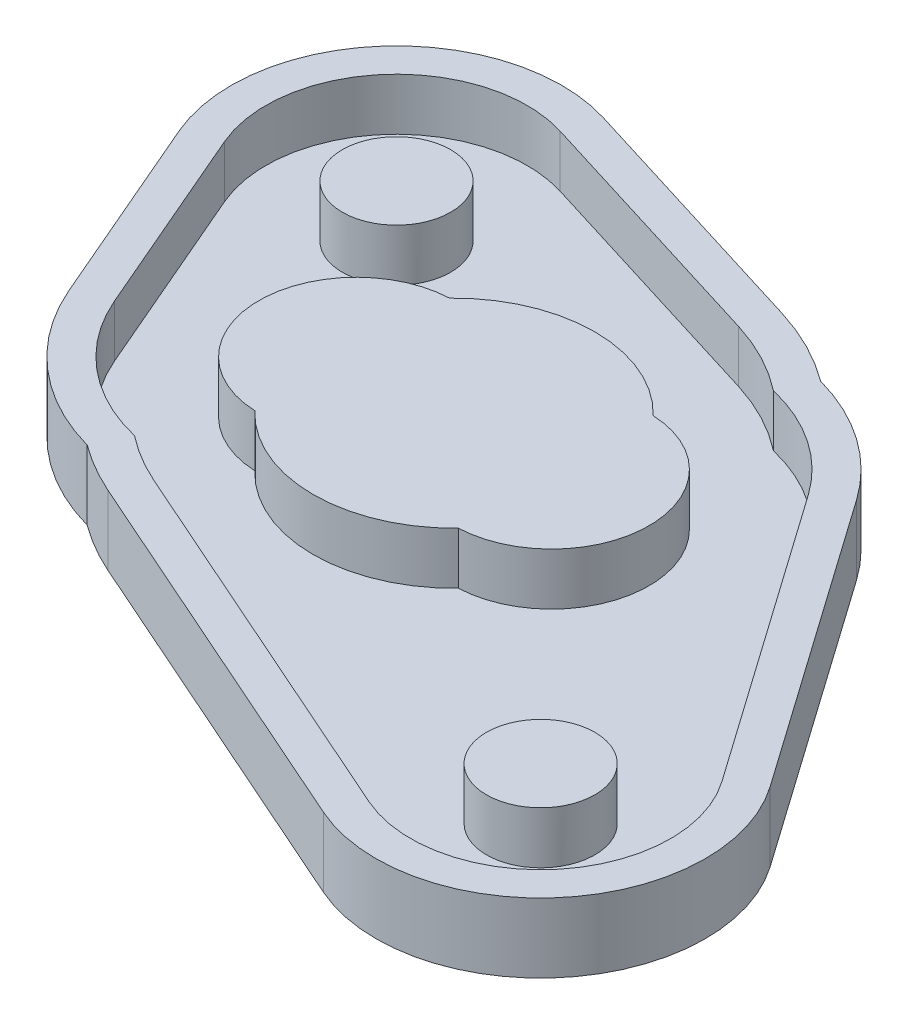
SolidWorks part; units mm, degrees
ref_plane "Front Plane" through (0, 0, 0) normal (0, 0, 1) x (1, 0, 0)
ref_plane "Top Plane" through (0, 0, 0) normal (0, 1, 0) x (1, 0, 0)
ref_plane "Right Plane" through (0, 0, 0) normal (1, 0, 0) x (0, 0, -1)
sketch "Sketch1" plane through (0, 0, 0) normal (0, 1, 0) x (1, 0, 0)
  line L0 (-5.625, 0) -> (5.625, 0) construction
  line L1 (0, 0) -> (0, 8.125) construction
  line L2 (0, -8.125) -> (0, -13.125) construction
  line L3 (-5.3106, -12.0026) -> (16.9654, -21.8587)
  line L4 (14.3146, 6.114) -> (26.1338, -10.6842)
  line L5 (12.5, -15) -> (20, -15) construction
  line L6 (-11.25, 0) -> (-13.2554, 0) construction
  line L7 (0, 8.125) -> (0, 9.9416) construction
  line L8 (20, -15) -> (0, 0) construction
  line L9 (0, 0) -> (-23.6642, 17.7481) construction
  line L10 (0, 0) -> (-14.4563, 10.8423) construction
  line L11 (0, 9.9416) -> (-13.2554, 9.9416) construction
  line L12 (-13.2554, 9.9416) -> (-13.2554, 0) construction
  line L13 (-20.1848, 6.9615) -> (-15.3857, -4.1977)
  line L14 (-11.0271, 17.1479) -> (3.8773, 12.5392)
  line L15 (-6.1198, -13.8316) -> (16.1562, -23.6876)
  line L16 (15.9503, 7.2649) -> (27.7695, -9.5334)
  line L17 (-10.4363, 19.0586) -> (4.4681, 14.45)
  line L18 (-22.0221, 6.1714) -> (-17.2229, -4.9878)
  arc A0 (-5.8681, -5.6197) -> (5.8681, -5.6197) centre (0, 0) ccw
  arc A1 (5.8681, -5.6197) -> (5.8681, 5.6197) centre (5.625, 0) ccw
  arc A2 (-5.8681, -5.6197) -> (-5.8681, 5.6197) centre (-5.625, 0) cw
  arc A3 (5.8681, 5.6197) -> (-5.8681, 5.6197) centre (0, 0) ccw
  arc A4 (14.3146, 6.114) -> (8.0903, 10.335) centre (5.625, 0) ccw
  arc A5 (8.0903, 10.335) -> (3.8773, 12.5392) centre (0, 0) ccw
  arc A6 (-8.0903, -10.335) -> (-15.3857, -4.1977) centre (-5.625, 0) cw
  arc A7 (-8.0903, -10.335) -> (-5.3106, -12.0026) centre (0, 0) ccw
  circle A8 centre (20, -15) radius 3.125
  arc A9 (16.9654, -21.8587) -> (26.1338, -10.6842) centre (20, -15) ccw
  circle A10 centre (-13.2554, 9.9416) radius 3.125
  arc A11 (-7.2424, 5.3875) -> (-7.221, 5.4158) centre (-13.2554, 9.9416) ccw
  arc A12 (-11.0271, 17.1479) -> (-20.1848, 6.9615) centre (-13.2554, 9.9416) ccw
  arc A13 (16.1562, -23.6876) -> (27.7695, -9.5334) centre (20, -15) ccw
  arc A14 (15.9503, 7.2649) -> (8.9792, 12.1713) centre (5.625, 0) ccw
  arc A15 (8.9792, 12.1713) -> (4.4681, 14.45) centre (0, 0) ccw
  arc A16 (-10.4363, 19.0586) -> (-22.0221, 6.1714) centre (-13.2554, 9.9416) ccw
  arc A17 (-8.9792, -12.1713) -> (-17.2229, -4.9878) centre (-5.625, 0) cw
  arc A18 (-8.9792, -12.1713) -> (-6.1198, -13.8316) centre (0, 0) ccw
  arc A19 (4.9792, 3.567) -> (-4.9792, 3.567) centre (0, 0) ccw
  arc A20 (-4.9792, -3.567) -> (-4.9792, 3.567) centre (-5.625, 0) cw
  arc A21 (-4.9792, -3.567) -> (4.9792, -3.567) centre (0, 0) ccw
  arc A22 (4.9792, -3.567) -> (4.9792, 3.567) centre (5.625, 0) ccw
  point P5 (0, 0)
  dimension "D1" = 6.25
  dimension "D2" = 2
  dimension "D3" = 2
extrude "Boss-Extrude1" add sketch "Sketch1" along normal blind 3 contours A17 A18 L15 A13 L16 A14 A15 L17 A16 L18 A12 L14 A5 A4 L4 A9 L3 A7 A6 L13 | A10 | A1 A3 A2 A0 A22 A21 A20 A19 | A8
sketch "Sketch2" plane through (0, 0, 0) normal (0, -1, 0) x (1, 0, 0)
  line L4 (-17.2229, 4.9878) -> (-22.0221, -6.1714)
  line L5 (-10.4363, -19.0586) -> (4.4681, -14.45)
  line L6 (15.9503, -7.2649) -> (27.7695, 9.5334)
  line L7 (16.1562, 23.6876) -> (-6.1198, 13.8316)
  line L8 (-17.2229, 4.9878) -> (-22.0221, -6.1714)
  line L9 (-10.4363, -19.0586) -> (4.4681, -14.45)
  line L10 (15.9503, -7.2649) -> (27.7695, 9.5334)
  line L11 (16.1562, 23.6876) -> (-6.1198, 13.8316)
  arc A6 (-8.9792, 12.1713) -> (-17.2229, 4.9878) centre (-5.625, 0) ccw
  arc A7 (-22.0221, -6.1714) -> (-10.4363, -19.0586) centre (-13.2554, -9.9416) ccw
  arc A8 (4.4681, -14.45) -> (8.9792, -12.1713) centre (0, 0) ccw
  arc A9 (8.9792, -12.1713) -> (15.9503, -7.2649) centre (5.625, 0) ccw
  arc A10 (27.7695, 9.5334) -> (16.1562, 23.6876) centre (20, 15) ccw
  arc A11 (-6.1198, 13.8316) -> (-8.9792, 12.1713) centre (0, 0) ccw
  arc A12 (-8.9792, 12.1713) -> (-17.2229, 4.9878) centre (-5.625, 0) ccw
  arc A13 (-22.0221, -6.1714) -> (-10.4363, -19.0586) centre (-13.2554, -9.9416) ccw
  arc A14 (4.4681, -14.45) -> (8.9792, -12.1713) centre (0, 0) ccw
  arc A15 (8.9792, -12.1713) -> (15.9503, -7.2649) centre (5.625, 0) ccw
  arc A16 (27.7695, 9.5334) -> (16.1562, 23.6876) centre (20, 15) ccw
  arc A17 (-6.1198, 13.8316) -> (-8.9792, 12.1713) centre (0, 0) ccw
  dimension "D1" = 0
extrude "Boss-Extrude2" add sketch "Sketch2" along normal blind 1
